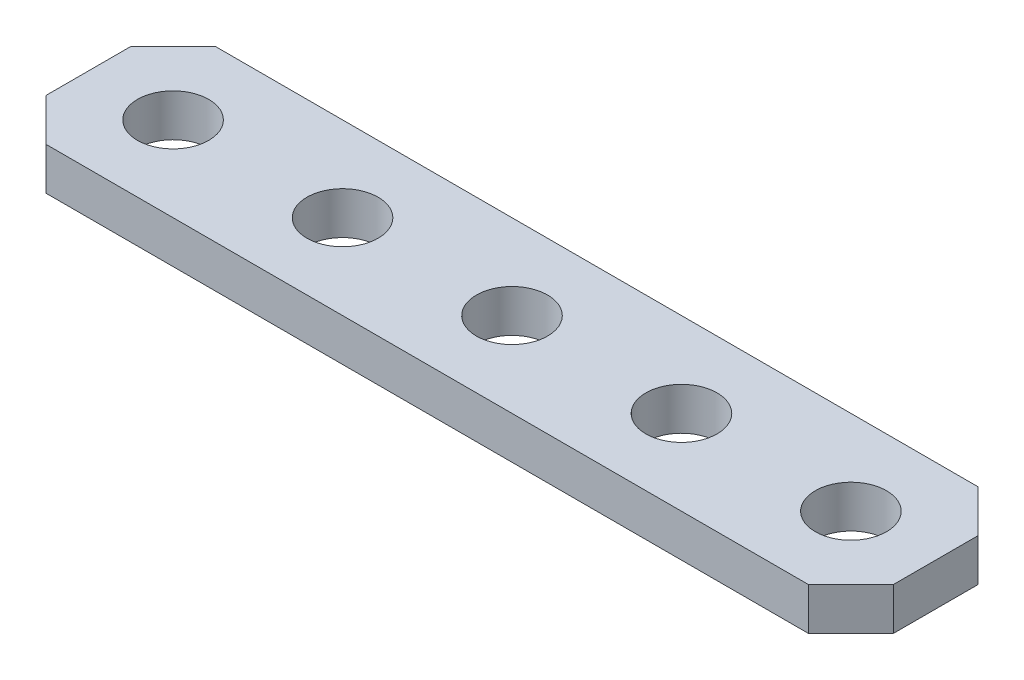
SolidWorks part; units mm, degrees
material "5052-H32"
ref_plane "Front" through (0, 0, 0) normal (0, 0, 1) x (1, 0, 0)
ref_plane "Top" through (0, 0, 0) normal (0, 1, 0) x (1, 0, 0)
ref_plane "Right" through (0, 0, 0) normal (1, 0, 0) x (0, 0, -1)
sketch "Sketch1" plane through (0, 0, 0) normal (0, 1, 0) x (1, 0, 0)
  line L0 (0, 6.35) -> (63.5, 6.35) construction
  line L1 (0, 0) -> (63.5, 0)
  line L2 (0, 0) -> (0, 12.7)
  line L3 (0, 12.7) -> (63.5, 12.7)
  line L4 (63.5, 0) -> (63.5, 12.7)
  line L5 (31.75, 6.35) -> (31.75, 12.7) construction
  line L6 (63.5, 0) -> (63.5, 12.7)
  circle A0 centre (19.05, 6.35) radius 2.667
  circle A1 centre (6.35, 6.35) radius 2.667
  circle A2 centre (57.15, 6.35) radius 2.667
  circle A3 centre (44.45, 6.35) radius 2.667
  circle A4 centre (31.75, 6.35) radius 2.667
  dimension "D2" = 5.334
  dimension "D1" = 12.7
  dimension "D3" = 12.7
  dimension "D4" = 6.35
  dimension "D5" = 12.7
extrude "Boss-Extrude1" add sketch "Sketch1" along normal blind 3.175 contours L1 L4 L3 L2 A2 A1 A0 A3
chamfer "Chamfer1" distance 3.175 angle 45 4 edges at (0, 1.5875, 0) (0, 1.5875, -12.7) (63.5, 1.5875, -12.7) (63.5, 1.5875, 0)
